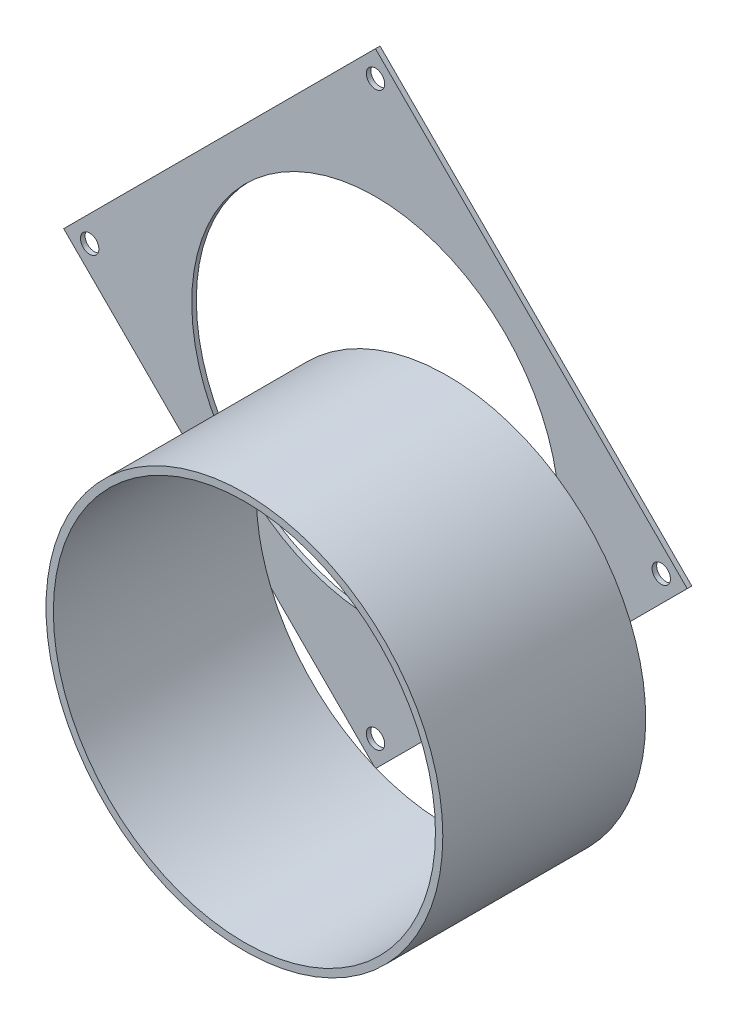
SolidWorks part; units mm, degrees
ref_plane "Front Plane" through (0, 0, 0) normal (0, 0, 1) x (1, 0, 0)
ref_plane "Top Plane" through (0, 0, 0) normal (0, 1, 0) x (1, 0, 0)
ref_plane "Right Plane" through (0, 0, 0) normal (1, 0, 0) x (0, 0, -1)
sketch "Sketch1" plane through (0, 0, 0) normal (0, 0, 1) x (1, 0, 0)
  circle A0 centre (24.8408, -46.2644) radius 66.04 construction
  circle A1 centre (24.8408, -46.2644) radius 66.04
  circle A2 centre (24.8408, -46.2644) radius 68.58
  dimension "D1" = 2.54
extrude "Boss-Extrude1" add sketch "Sketch1" along normal up to surface (70.1402 mm away)
sketch "Sketch2" plane through (0, 0, -70.1402) normal (0, 0, -1) x (-1, 0, 0)
  line L0 (0, 0) -> (0, -93.9757) construction
  line L1 (0, 0) -> (122.1618, 0) construction
  line L2 (0, -107.7631) -> (107.7631, 0)
  line L3 (0, 107.7631) -> (107.7631, 0)
  line L4 (0, 107.7631) -> (-107.7631, 0)
  line L5 (0, -107.7631) -> (-107.7631, 0)
  circle A0 centre (0, 98.7828) radius 3.175
  circle A1 centre (98.7828, 0) radius 3.175
  circle A2 centre (0, -98.7828) radius 3.175
  circle A3 centre (-98.7828, 0) radius 3.175
  circle A4 centre (0, 0) radius 63.5
  point P19 (0, 0)
  dimension "D3" = 6.35
  dimension "D4" = 6.35
  dimension "D5" = 6.35
  dimension "D7" = 127
  dimension "D1" = 152.4
  dimension "D2" = 45
  dimension "D6" = 4
extrude "Boss-Extrude2" add sketch "Sketch2" along normal blind 1.5875
